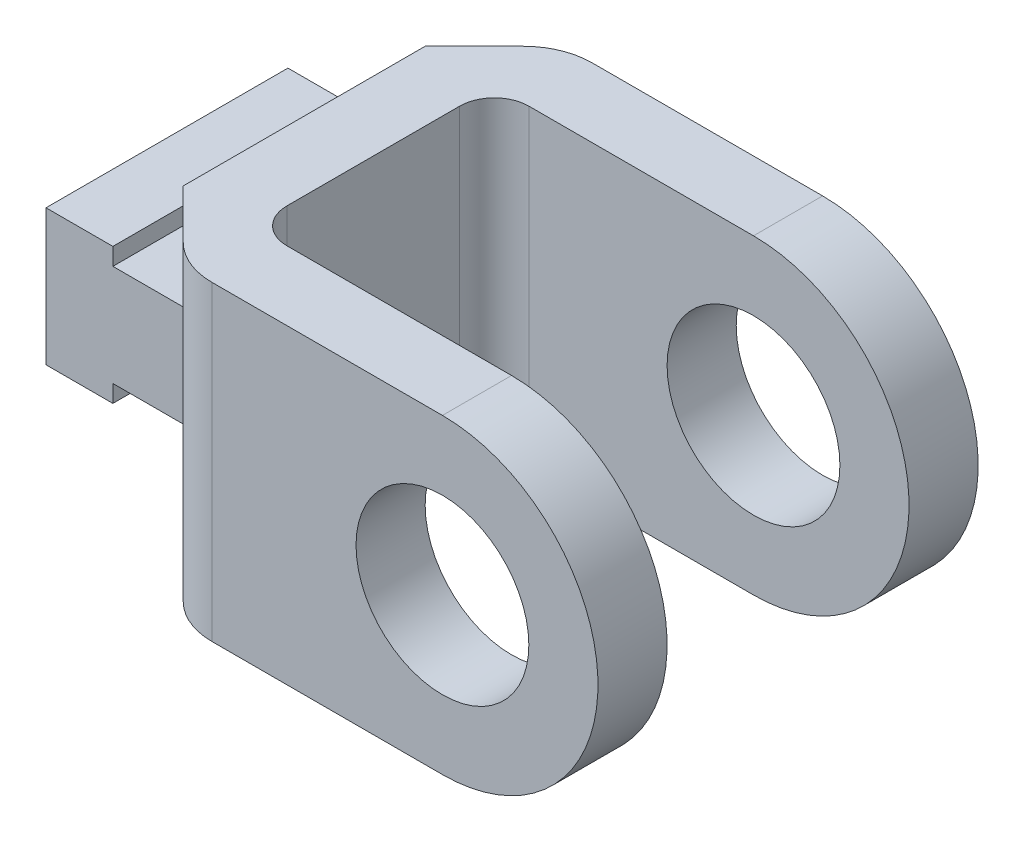
SolidWorks part; units mm, degrees
ref_plane "Front Plane" through (0, 0, 0) normal (0, 0, 1) x (1, 0, 0)
ref_plane "Top Plane" through (0, 0, 0) normal (0, 1, 0) x (1, 0, 0)
ref_plane "Right Plane" through (0, 0, 0) normal (1, 0, 0) x (0, 0, -1)
sketch "Sketch1" plane through (0, 0, 0) normal (0, 0, 1) x (1, 0, 0)
  line L7 (-1, -4.5) -> (1, -4.5)
  line L11 (-7.7473, 0) -> (6.5352, 0) construction
  line L18 (-1, 4.5) -> (1, 4.5)
  line L19 (1, -4.5) -> (1, 4.5)
  line L20 (-1, -4.5) -> (1, 4.5) construction
  line L21 (-1, 4.5) -> (1, -4.5) construction
  line L24 (-1, 4.5) -> (-1, -4.5)
  point P0 (0, 0)
  point P3 (-2.525, 0)
  point P5 (0, 0)
  point P12 (-5, 0)
  dimension "D1" = 2
  dimension "D2" = 9
extrude "Boss-Extrude2" add sketch "Sketch1" along normal blind 7
ref_plane "Notch Plane" through (0, 0, 3.5) normal (0, 0, 1) x (1, 0, 0)
sketch "Sketch5" plane through (0, 0, 3.5) normal (0, 0, 1) x (1, 0, 0)
  line L0 (4.769, 0) -> (-6.9633, 0) construction
  line L1 (-1, 4.5) -> (-1, -4.5) construction
  line L2 (-3.035, -1.4675) -> (-1, -1.4675)
  line L4 (-3.035, 1.4675) -> (-1, 1.4675)
  line L5 (-1, -1.4675) -> (-1, 1.4675)
  line L6 (-3.035, -1.4675) -> (-1, 1.4675) construction
  line L7 (-3.035, 1.4675) -> (-1, -1.4675) construction
  line L8 (-3.035, 1.4675) -> (-3.035, 1.9675)
  line L9 (-4.97, -1.9675) -> (-3.035, -1.9675)
  line L10 (-4.97, -1.9675) -> (-4.97, 1.9675)
  line L11 (-4.97, 1.9675) -> (-3.035, 1.9675)
  line L12 (-3.035, -1.9675) -> (-3.035, -1.4675)
  line L13 (-4.97, -1.9675) -> (-3.035, 1.9675) construction
  line L14 (-4.97, 1.9675) -> (-3.035, -1.9675) construction
  point P3 (-2.0175, 0)
  point P10 (-4.0025, 0)
  dimension "D1" = 2.035
  dimension "D2" = 2.935
  dimension "D3" = 1.935
  dimension "D4" = 3.935
extrude "Boss-Extrude4" add sketch "Sketch5" along normal through all and the other way through all
sketch "Sketch2" plane through (0, 0, 0) normal (0, 0, 1) x (1, 0, 0)
  line L0 (-1, 4.5) -> (-1, 1.4675) construction
  line L1 (-1, 4.5) -> (8.5, 4.5)
  line L2 (-1, 4.5) -> (-1, -4.5)
  line L3 (-1, -4.5) -> (8.5, -4.5)
  arc A0 (8.5, -4.5) -> (8.5, 4.5) centre (8.5, 0) ccw
  circle A1 centre (8.5, 0) radius 2.5
  circle A2 centre (8.5, 0) radius 6.5 construction
  point P1 (13, 0)
  point P11 (2, 0)
  dimension "D3" = 5
  dimension "D2" = 13
  dimension "D1" = 14
extrude "Boss-Extrude3" add sketch "Sketch2" against normal blind 2
ref_plane "Plane1" through (0, 4.5, 0) normal (0, 1, 0) x (1, 0, 0)
sketch "Sketch4" plane through (0, 4.5, 0) normal (0, 1, 0) x (1, 0, 0)
  line L0 (1, -0.5237) -> (1, 2.9724) construction
  line L1 (8.5, 2) -> (-1, 2) construction
  line L2 (-1, 0) -> (1, 2)
  line L3 (1, 2) -> (-1, 2)
  line L4 (-1, 0) -> (-1, 2)
  line L5 (1, -7) -> (1, 0) construction
  point P0 (1, -0.5237)
  point P4 (1, 2)
extrude "Cut-Extrude3" cut sketch "Sketch4" against normal through all
fillet "Fillet1" radius 1 1 edges at (1, 0, 0)
fillet "Fillet2" radius 2 1 edges at (1, 0, -2)
ref_plane "Plane2" through (0, 0, 3.5) normal (0, 0, 1) x (1, 0, 0)
mirror "Mirror2" about plane through (0, 0, 3.5) normal (0, 0, 1) of "Boss-Extrude2", "Fillet2", "Cut-Extrude3", "Boss-Extrude3"
fillet "Fillet3" radius 1 1 edges at (1, 0, 7)
